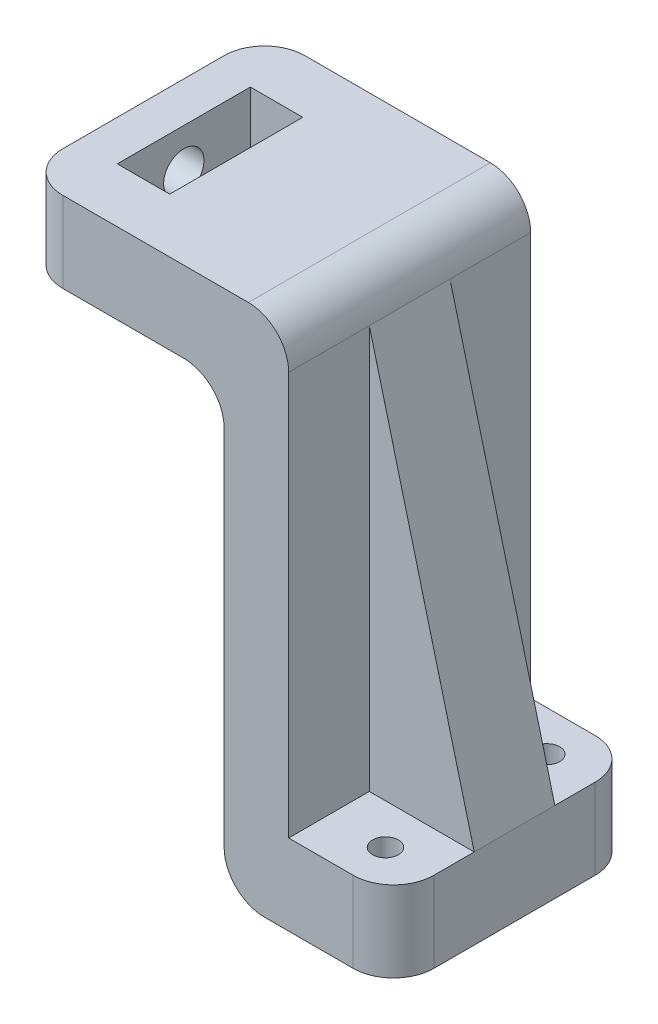
SolidWorks part; units mm, degrees
ref_plane "Front Plane" through (0, 0, 0) normal (0, 0, 1) x (1, 0, 0)
ref_plane "Top Plane" through (0, 0, 0) normal (0, 1, 0) x (1, 0, 0)
ref_plane "Right Plane" through (0, 0, 0) normal (1, 0, 0) x (0, 0, -1)
sketch "Sketch1" plane through (0, 0, 0) normal (0, 1, 0) x (1, 0, 0)
  line L14 (-15, 5) -> (6, 5)
  line L16 (6, 5) -> (6, -25)
  line L17 (6, -25) -> (-15, -25)
  line L19 (0, 0) -> (0, -5.3774) construction
  line L20 (-15, 5) -> (-15, -25)
  line L21 (-15, -10) -> (6, -10) construction
  circle A4 centre (0, 0) radius 1.6
  circle A5 centre (0, -20) radius 1.6
  dimension "D1" = 3.2
  dimension "D3" = 21
  dimension "D2" = 20
  dimension "D4" = 30
  dimension "D5" = 10
  dimension "D6" = 6
extrude "Boss-Extrude3" add sketch "Sketch1" along normal blind 10
sketch "Sketch3" plane through (0, 10, 0) normal (0, 1, 0) x (1, 0, 0)
  line L0 (-15, -25) -> (6, -25) construction
  line L1 (-15, 5) -> (-7, 5)
  line L2 (-15, 5) -> (-15, -25)
  line L3 (-15, -25) -> (-7, -25)
  line L4 (-7, 5) -> (-7, -25)
  dimension "D1" = 8
extrude "Boss-Extrude4" add sketch "Sketch3" along normal blind 55
sketch "Sketch4" plane through (-15, 0, 0) normal (-1, 0, 0) x (0, 0, 1)
  line L0 (25, 65) -> (25, 0) construction
  line L1 (-5, 65) -> (25, 65)
  line L2 (-5, 65) -> (-5, 55)
  line L3 (-5, 55) -> (25, 55)
  line L4 (25, 65) -> (25, 55)
  dimension "D1" = 10
extrude "Boss-Extrude5" add sketch "Sketch4" along normal blind 25
sketch "Sketch5" plane through (0, 65, 0) normal (0, 1, 0) x (1, 0, 0)
  line L0 (6, -25) -> (6, 5) construction
  line L1 (-35, -1.75) -> (-28.5, -1.75)
  line L2 (-35, -1.75) -> (-35, -18.25)
  line L3 (-35, -18.25) -> (-28.5, -18.25)
  line L4 (-28.5, -1.75) -> (-28.5, -18.25)
  line L5 (-35, -1.75) -> (-28.5, -18.25) construction
  line L6 (-35, -18.25) -> (-28.5, -1.75) construction
  line L7 (6, -10) -> (-38.965, -10) construction
  line L8 (-40, -25) -> (-40, 5) construction
  point P0 (-31.75, -10)
  dimension "D1" = 6.5
  dimension "D2" = 16.5
  dimension "D3" = 5
extrude "Cut-Extrude1" cut sketch "Sketch5" against normal up to next
sketch "Sketch7" plane through (-40, 0, 0) normal (-1, 0, 0) x (0, 0, 1)
  line L0 (-5, 65) -> (-5, 55) construction
  line L1 (25, 55) -> (25, 65) construction
  line L2 (-5, 60) -> (25, 60) construction
  line L3 (10, 65) -> (10, 55) construction
  line L4 (25, 65) -> (-5, 65) construction
  line L5 (-5, 55) -> (25, 55) construction
  circle A0 centre (10, 60) radius 2.5
  dimension "D1" = 5
extrude "Cut-Extrude2" cut sketch "Sketch7" against normal blind 17.2
fillet "Fillet2" radius 5 7 edges at (-15, 55, 10) (-7, 65, 10) (6, 5, -5) (6, 5, 25) (-40, 60, -5) (-40, 60, 25) (-15, 0, 10)
sketch "Sketch8" plane through (0, 0, 25) normal (0, 0, 1) x (1, 0, 0)
  line L2 (-7, 10) -> (-7, 60)
  line L3 (-7, 60) -> (6, 10)
  line L4 (6, 10) -> (-7, 10)
extrude "Boss-Extrude7" add sketch "Sketch8" against normal offset from surface (10 mm away) 10 from offset 10 up to face at (-13.9059, 34.185, -5)
